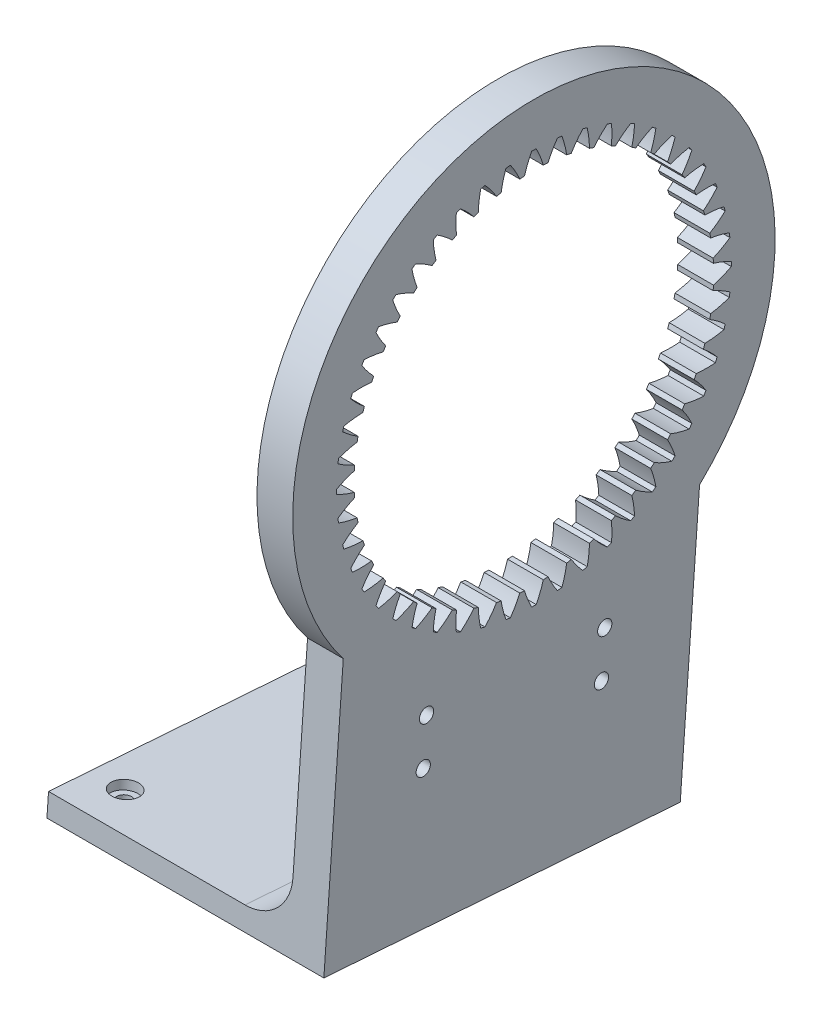
SolidWorks part; units mm, degrees
material "PLA personnalisé"
ref_plane "Plane1" through (0, 0, 0) normal (0, 0, 1) x (1, 0, 0)
ref_plane "Plane2" through (0, 0, 0) normal (0, 1, 0) x (1, 0, 0)
ref_plane "Plane3" through (0, 0, 0) normal (1, 0, 0) x (0, 0, -1)
other "Configuration Table"
sketch "HoldingSke" plane through (0, 0, 0) normal (0, 1, 0) x (1, 0, 0)
  line L0 (0, 0) -> (0.3824, -0.4247)
  line L1 (-15, 0) -> (100, 0) construction
  line L2 (0, 0) -> (-2.1039, 2.3779)
  line L3 (0, 0) -> (-11.863, 4.5341)
  line L4 (0, 0) -> (5.7786, 6.4178)
  line L5 (0, 0) -> (-23.7986, -8.8762)
  line L6 (0, 0) -> (-10.5278, -7.1032)
  line L7 (-2.1039, 2.3779) -> (3.3635, 27.1825)
  line L8 (-76.2, 4.1279) -> (-54.61, 4.1279)
  line L9 (-71.009, 38.7566) -> (-53.1078, 45.2721)
  line L10 (-76.2, 71.12) -> (104.1128, 71.12)
  line L11 (0, 0) -> (-8, 0)
  line L12 (-76.2, 101.6) -> (-76.147, 101.6)
  line L13 (24.9733, 27.94) -> (52.9518, 28.4284)
  line L14 (24.9733, 27.94) -> (24.9743, 27.94)
  line L15 (24.9733, 27.94) -> (100.4006, 29.5858)
  circle A0 centre (0, 0) radius 54
  circle A1 centre (0, 0) radius 12.7
  circle A2 centre (0, 0) radius 12.7
  dimension "MHD" = 25.4
  dimension "Hub_dia" = 25.4
  dimension "Diameter" = 108
  dimension "Num_teeth" = 48
  dimension "Pitch" = 0.5714
  dimension "Overall_len" = 25.4
  dimension "Show_teeth" = 48
  dimension "Thickness" = 12.7
  dimension "OAL" = 25.4001
  dimension "T_dim" = 21.59
  dimension "Ap" = 20
  dimension "H" = 19.05
  dimension "Pitch_radius" = 180.3128
  dimension "Width" = 8
  dimension "Backlash" = 0.053
  dimension "Addendum_fac" = 1
  dimension "Dedendum_fac" = 1.25
  dimension "Clearance_fac" = 0.25
  dimension "Dedendum_add" = 0.001
  dimension "Module" = 1.75
sketch "BasProSke" plane through (0, 0, 0) normal (0, 1, 0) x (1, 0, 0)
  line L0 (-10, 0) -> (60, 0) construction
  line L1 (0, 40.25) -> (0, 54)
  line L2 (0, 40.25) -> (8, 40.25)
  line L3 (8, 40.25) -> (8, 54)
  line L4 (8, 54) -> (0, 54)
  dimension "Diameter" = 108
  dimension "Thickness" = 8
  dimension "Inside_diameter" = 80.5
revolve "Base-Revolve" add sketch "BasProSke" angle 360 about L0
sketch "TooCutSke" plane through (0, 0, 0) normal (1, 0, 0) x (0, 0, -1)
  line L3 (1.5067, 41.973) -> (1.5067, 53.6633) construction
  line L4 (0, 0) -> (0, 59.563) construction
  line L5 (0, 0) -> (-4.4688, 68.1812) construction
  line L6 (-18.0846, 34.4113) -> (35.4386, 37.9194) construction
  circle A0 centre (0, 0) radius 42 construction
  circle A1 centre (0, 0) radius 44.1885 construction
  circle A2 centre (0, 0) radius 35.5204 construction
  circle A3 centre (0, 0) radius 40.2246 construction
  arc A4 (2.1106, 40.1692) -> (0.502, 44.1856) centre (-18.0846, 34.4113) ccw
  arc A5 (2.1106, 40.1692) -> (-2.1106, 40.1692) centre (0, 0) ccw
  arc A6 (0.502, 44.1856) -> (-0.502, 44.1856) centre (0, 0) ccw
  arc A7 (-0.502, 44.1856) -> (-2.1106, 40.1692) centre (18.0846, 34.4113) ccw
  dimension "Pitch_dia" = 84
  dimension "Base_dia" = 71.0408
  dimension "Root_dia" = 88.377
  dimension "Overcut_dia" = 80.4492
  dimension "Flank_rad" = 21
  dimension "Half_ang" = 3.75
  dimension "Half_CT" = 1.5067
extrude "ToothCut" cut sketch "TooCutSke" along normal through all
fillet "Breaks" [suppressed] radius 0.175
fillet "RootFillets" [suppressed] radius 0.4385
pattern_circular "TeethCuts" count 48 over 360 about axis through (0, 0, 0) along (1, 0, 0) of "RootFillets", "Breaks", "ToothCut"
sketch "Esquisse1" plane through (8, 0, 0) normal (1, 0, 0) x (0, 0, -1)
  circle A0 centre (0, 0) radius 44.1885
  circle A1 centre (0, 0) radius 48.6885
  circle A2 centre (3.5329, 48.5602) radius 1.6
  dimension "D1" = 4.5
  dimension "D2" = 3.2
extrude "Enlèv. mat.-Extru.1" cut sketch "Esquisse1" against normal blind 10 contours A2
pattern_circular "Répétition circulaire1" count 6 over 360 about axis through (0, 0, 0) along (1, 0, 0) of "Enlèv. mat.-Extru.1"
sketch "Esquisse2" plane through (8, 0, 0) normal (1, 0, 0) x (0, 0, -1)
  line L0 (-41.8261, -21.3656) -> (37.963, -27.1706) construction
  line L1 (-41.8261, -21.3656) -> (37.963, -27.1706)
  line L2 (-41.8261, -21.3656) -> (-47.0256, -92.8324)
  line L3 (37.963, -27.1706) -> (32.7635, -98.6374)
  line L4 (-47.0256, -92.8324) -> (32.7635, -98.6374)
  line L5 (0, 0) -> (-7.131, -95.7349) construction
  line L6 (-44.4258, -57.099) -> (-4.4748, -60.0748) construction
  line L7 (35.3633, -62.904) -> (-4.4748, -60.0748) construction
  circle A0 centre (0, 0) radius 54
  dimension "D1" = 96
  dimension "D2" = 80
extrude "Boss.-Extru.1" add sketch "Esquisse2" against normal through all contours A0 L2 L4 L3
sketch "Esquisse3" plane through (8, 0, 0) normal (1, 0, 0) x (0, 0, -1)
  circle A0 centre (-3.5329, -48.5602) radius 2.4787
extrude "Boss.-Extru.2" add sketch "Esquisse3" against normal blind 8
pattern_circular "Répétition circulaire3" count 6 over 360 about axis through (8, 0, 0) along (-1, 0, 0) of "Boss.-Extru.2"
sketch "Esquisse4" plane through (0, 0, 0) normal (-1, 0, 0) x (0, 0, 1)
  line L0 (7.131, -95.7349) -> (0, 0) construction
  line L1 (47.0256, -92.8324) -> (-32.7635, -98.6374) construction
  line L2 (44.0455, -51.8715) -> (-35.7336, -57.8141) construction
  line L3 (42.6786, -33.0838) -> (47.0256, -92.8324) construction
  line L4 (-37.084, -39.2527) -> (-32.7635, -98.6374) construction
  line L5 (-35.008, -67.7877) -> (44.7711, -61.8452) construction
  circle A0 centre (-15.8593, -56.3337) radius 1.6
  circle A1 centre (-15.1165, -66.3061) radius 1.6
  circle A2 centre (24.773, -63.3348) radius 1.6
  circle A3 centre (24.0302, -53.3624) radius 1.6
  dimension "D3" = 3.2
  dimension "D4" = 3.2
  dimension "D1" = 55
  dimension "D2" = 10
  dimension "D5" = 20
  dimension "D6" = 20
extrude "Enlèv. mat.-Extru.2" cut sketch "Esquisse4" against normal blind 10
sketch "Esquisse5" plane through (8, 0, 0) normal (1, 0, 0) x (0, 0, -1)
  line L0 (-47.0256, -92.8324) -> (32.7635, -98.6374)
  line L1 (32.7635, -98.6374) -> (33.1264, -93.6506)
  line L2 (37.084, -39.2527) -> (32.7635, -98.6374) construction
  line L3 (33.1264, -93.6506) -> (-46.6628, -87.8456)
  line L4 (-42.6786, -33.0838) -> (-47.0256, -92.8324) construction
  line L5 (-46.6628, -87.8456) -> (-47.0256, -92.8324)
  dimension "D1" = 5
extrude "Boss.-Extru.3" add sketch "Esquisse5" against normal blind 54 from offset 8 offset against normal yes
fillet "Congé1" radius 10 1 edges at (0, -90.7481, 6.7682)
sketch "Esquisse6" plane through (0, -90.7601, 6.6032) normal (0, 0.9974, -0.0726) x (1, 0, 0)
  line L0 (-54, -0.1655) -> (-140.1065, -0.1655) construction
  line L1 (-54, 39.8345) -> (-54, -40.1655) construction
  line L2 (-54, -0.1655) -> (-10, -0.1655) construction
  line L3 (-10, -40.1655) -> (-10, 39.8345) construction
  circle A0 centre (-64, -0.1655) radius 35
  circle A1 centre (-29, -0.1655) radius 3
  circle A2 centre (-46.5, -30.4764) radius 3
  circle A3 centre (-81.5, -30.4764) radius 3
  circle A4 centre (-99, -0.1655) radius 3
  circle A5 centre (-81.5, 30.1454) radius 3
  circle A6 centre (-46.5, 30.1454) radius 3
  point P23 (-64, -0.1655)
  dimension "D2" = 70
  dimension "D3" = 6
  dimension "D1" = 10
  dimension "D4" = 6
extrude "Enlèv. mat.-Extru.3" cut sketch "Esquisse6" against normal blind 2 contours A2 | A1 | A6
sketch "Esquisse7" plane through (0, -90.7601, 6.6032) normal (0, 0.9974, -0.0726) x (1, 0, 0)
  circle A0 centre (-29, -0.1655) radius 1.6
  circle A1 centre (-46.5, 30.1454) radius 1.6
  circle A2 centre (-46.5, -30.4764) radius 1.6
  dimension "D1" = 3.2
  dimension "D2" = 3.2
  dimension "D3" = 3.2
extrude "Enlèv. mat.-Extru.4" cut sketch "Esquisse7" against normal blind 5
equation "' \"Module@HoldingSke\" = 6.35"
equation "' \"Num_teeth@HoldingSke\" = 24"
equation "' \"Ap@HoldingSke\" =  14.5"
equation "' \"Ap@HoldingSke\" = 14.5"
equation "' \"Width@HoldingSke\" = 12"
equation "' \"Diameter@HoldingSke\" = 8 * 25.4"
equation "' \"Show_teeth@HoldingSke\" = 100"
equation "' \"Backlash@HoldingSke\" = 0.009 * 25.4"
equation "' \"Addendum_fac@HoldingSke\" = 1.0"
equation "' \"Dedendum_fac@HoldingSke\" = 1.25"
equation "' \"Dedendum_add@HoldingSke\" = 0.00005 * 25.4"
equation "' \"Clearance_fac@HoldingSke\" = 0.25"
equation "\"Pitch@HoldingSke\" = 1 / \"Module@HoldingSke\" "
equation "\"Overcut_dia@TooCutSke\" = (\"Num_teeth@HoldingSke\" - 2 * \"Addendum_fac@HoldingSke\") / \"Pitch@HoldingSke\" - 0.002 * 25.4"
equation "\"Pitch_dia@TooCutSke\" = \"Num_teeth@HoldingSke\" / \"Pitch@HoldingSke\""
equation "\"Base_dia@TooCutSke\" = \"Num_teeth@HoldingSke\" / \"Pitch@HoldingSke\" * cos((\"Ap@HoldingSke\"  * 3.14159265 / 180)) * 0.90"
equation "\"Root_dia@TooCutSke\" = \"Num_teeth@HoldingSke\"  / \"Pitch@HoldingSke\" + 2 *  \"Dedendum_fac@HoldingSke\"/ \"Pitch@HoldingSke\" + \"Dedendum_add@HoldingSke\" * 2"
equation "\"Half_ang@TooCutSke\" = 180 / \"Num_teeth@HoldingSke\""
equation "\"Half_CT@TooCutSke\" = \"Num_teeth@HoldingSke\" / \"Pitch@HoldingSke\" * sin((3.14159265 / 2 / \"Num_teeth@HoldingSke\")) / 2 + 10 * \"Backlash@HoldingSke\" / 4"
equation "\"Flank_rad@TooCutSke\" = \"Num_teeth@HoldingSke\" / \"Pitch@HoldingSke\" / 4"
equation "\"Radius@RootFillets\"= \"Clearance_fac@HoldingSke\" / \"Pitch@HoldingSke\" + \"Dedendum_add@HoldingSke\""
equation "\"Break_rad@Breaks\" = 0.02 / \"Pitch@HoldingSke\" * 5"
equation "\"Num_teeth@TeethCuts\" = int( \"Show_teeth@HoldingSke\" ) + 1"
equation "\"Num_teeth@TeethCuts\" = ((sgn( \"Num_teeth@TeethCuts\" - \"Num_teeth@HoldingSke\" )-1)*( \"Num_teeth@TeethCuts\" - \"Num_teeth@HoldingSke\" ))/-2+ \"Num_teeth@HoldingSke\""
equation "\"Num_teeth@TeethCuts\" = ((sgn( \"Num_teeth@TeethCuts\" - 2.0)+1)*( \"Num_teeth@TeethCuts\" - 2.0))/2 +2.0"
equation "\"Angle@TeethCuts\" = 360.0 / \"Num_teeth@HoldingSke\""
equation "\"Diameter@BasProSke\" = \"Num_teeth@HoldingSke\"  / \"Pitch@HoldingSke\" + 2 *  \"Dedendum_fac@HoldingSke\"/ \"Pitch@HoldingSke\" + \"Dedendum_add@HoldingSke\" * 2 + 0.002 * 25.4"
equation "\"Diameter@BasProSke\" = ((sgn( \"Diameter@BasProSke\"  - \"Diameter@HoldingSke\" )+1)*( \"Diameter@BasProSke\"  - \"Diameter@HoldingSke\" ))/2 + \"Diameter@HoldingSke\""
equation "\"Inside_diameter@BasProSke\" =  (\"Num_teeth@HoldingSke\" - 2 * \"Addendum_fac@HoldingSke\") / \"Pitch@HoldingSke\" "
equation "\"Thickness@BasProSke\"  = \"Width@HoldingSke\""
